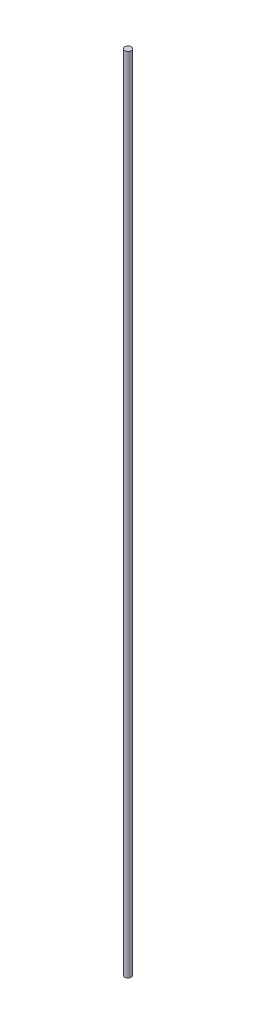
SolidWorks part; units mm, degrees
ref_plane "Front Plane" through (0, 0, 0) normal (0, 0, 1) x (1, 0, 0)
ref_plane "Top Plane" through (0, 0, 0) normal (0, 1, 0) x (1, 0, 0)
ref_plane "Right Plane" through (0, 0, 0) normal (1, 0, 0) x (0, 0, -1)
sketch "Sketch1" plane through (0, 0, 0) normal (0, 1, 0) x (1, 0, 0)
  circle A0 centre (0, 0) radius 2.5
  dimension "D1" = 5
extrude "Boss-Extrude1" add sketch "Sketch1" along normal blind 600
